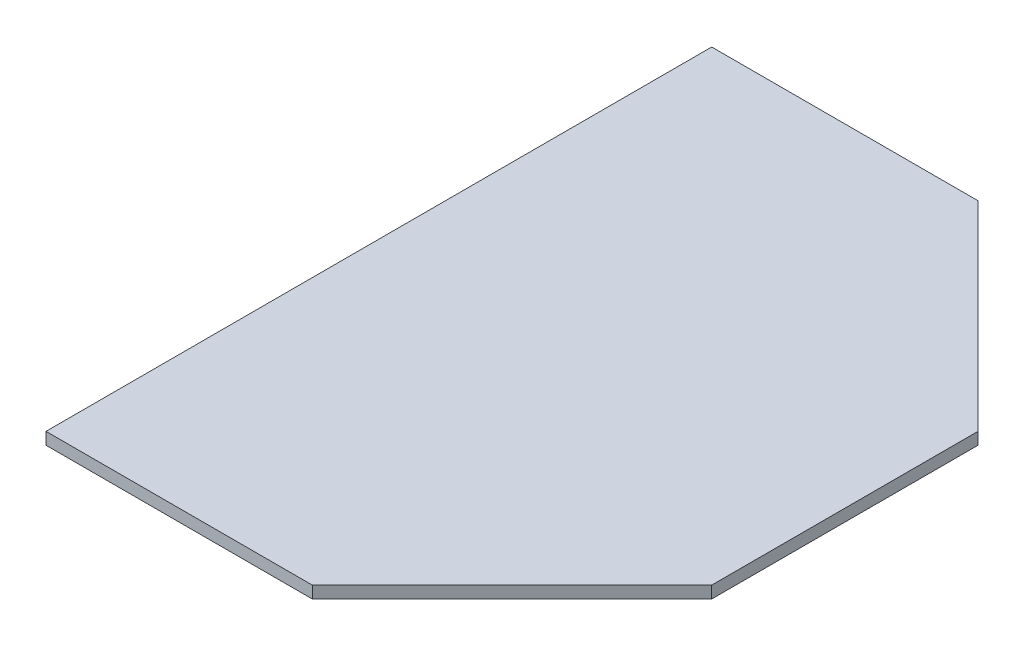
SolidWorks part; units mm, degrees
ref_plane "Front Plane" through (0, 0, 0) normal (0, 0, 1) x (1, 0, 0)
ref_plane "Top Plane" through (0, 0, 0) normal (0, 1, 0) x (1, 0, 0)
ref_plane "Right Plane" through (0, 0, 0) normal (1, 0, 0) x (0, 0, -1)
sketch "Sketch1" plane through (0, 0, 0) normal (0, 1, 0) x (1, 0, 0)
  line L1 (0, 0) -> (254, 0)
  line L2 (0, 0) -> (0, 254)
  line L3 (0, 254) -> (254, 254)
  line L4 (254, 0) -> (254, 254)
  dimension "D1" = 254
  dimension "D2" = 254
extrude "Boss-Extrude1" add sketch "Sketch1" along normal blind 4.6
sketch "Sketch2" plane through (0, 4.6, 0) normal (0, 1, 0) x (1, 0, 0)
  line L0 (0, 254) -> (76.2, 254) construction
  line L1 (254, 254) -> (0, 254) construction
  line L2 (0, 254) -> (0, 177.8) construction
  line L3 (0, 254) -> (0, 0) construction
sketch "Sketch4" plane through (0, 4.6, 0) normal (0, 1, 0) x (1, 0, 0)
  line L0 (76.2, 254) -> (0, 177.8)
  line L1 (0, 177.8) -> (0, 254)
  line L2 (0, 254) -> (76.2, 254)
extrude "Cut-Extrude2" cut sketch "Sketch4" against normal through all
sketch "Sketch5" plane through (0, 4.6, 0) normal (0, 1, 0) x (1, 0, 0)
  line L0 (177.8, 254) -> (254, 254) construction
  line L1 (254, 254) -> (76.2, 254) construction
  line L2 (254, 254) -> (254, 177.8) construction
  line L3 (254, 0) -> (254, 254) construction
  line L4 (177.8, 254) -> (254, 177.8)
  line L5 (254, 177.8) -> (254, 254)
  line L6 (254, 254) -> (177.8, 254)
extrude "Cut-Extrude3" cut sketch "Sketch5" against normal blind 4.826
sketch "Sketch9" plane through (0, 4.6, 0) normal (0, 1, 0) x (1, 0, 0)
  line L0 (0, 76.2) -> (0, 0)
  line L1 (0, 177.8) -> (0, 0) construction
  line L2 (0, 0) -> (76.2, 0)
  line L3 (0, 0) -> (254, 0) construction
  line L4 (76.2, 0) -> (0, 76.2)
  dimension "D1" = 76.2
  dimension "D2" = 76.2
extrude "Cut-Extrude5" cut sketch "Sketch9" against normal blind 4.826
sketch "Sketch11" plane through (0, 4.6, 0) normal (0, 1, 0) x (1, 0, 0)
  line L0 (254, 76.2) -> (254, 0)
  line L1 (254, 0) -> (254, 177.8) construction
  line L2 (254, 0) -> (177.8, 0)
  line L3 (76.2, 0) -> (254, 0) construction
  line L4 (177.8, 0) -> (254, 76.2)
  dimension "D1" = 76.2
  dimension "D2" = 76.2
extrude "Cut-Extrude6" cut sketch "Sketch11" against normal blind 4.826
ref_plane "Plane1" through (0, 0, -127) normal (0, 0, -1) x (-1, 0, 0)
ref_plane "Plane2" through (127, 0, 0) normal (-1, 0, 0) x (0, 0, 1)
sketch "Sketch12" plane through (0, 0, 0) normal (0, -1, 0) x (1, 0, 0)
  line L0 (76.2, 0) -> (76.2, -254)
  line L1 (76.2, -254) -> (0, -177.8)
  line L2 (0, -177.8) -> (0, -76.2)
  line L3 (0, -76.2) -> (76.2, 0)
extrude "Cut-Extrude7" cut sketch "Sketch12" against normal through all
equation "\"MDF\"= 4.8mm"
equation "\"Foamcore\"= 4.6mm"
equation "\"GMaterial\"= \"MDF\""
equation "\"D1@Boss-Extrude1\"=\"Foamcore\""
equation "\"PCB\" = 1.6mm"
equation "\"BaseWidth\" = 10in"
equation "\"SkidLength\" = 1in"
equation "\"SkidClearance\" = 0.4in"
equation "\"MotorMountLength\" = 2in"
equation "\"MotorMountWidth\" = \"GMaterial\""
equation "\"MotorMountHeight\" = 2.25in"
equation "\"UnoStackWidth\" = 77.4mm"
equation "\"UnoStackLength\" = 79.8mm"
equation "\"UnoStackHeight\" = 34.2mm"
equation "\"TallHexRiserHeight\" = 22.2mm"
equation "\"PingPongBallSize\" = 40mm"
equation "\"BarrelLength\" = 9in"
equation "\"BarrelSize\" = \"PingPongBallSize\""
equation "\"PlatformLength\" = 4in"
equation "\"PlatformWidth\" = 6in"
equation "\"WheelDiameter\"=2.99213"
equation "\"ServoMountHeight\"=2.49223"
equation "\"ServoGearHeight\" = 0.95330261in"
equation "\"ServoMountLength\"= 1.53774"
equation "\"PivotHoleRadius\"= 0.616358"
equation "\"PlatformMountHeight\" = 3.19"
equation "\"TensionOffSet\"= .3mm"
equation "\"MotorMountWedge\"=0.333333"
equation "\"LaserCutterOffset\"= .3mm"
equation "\"BumperWidth\"=11"
equation "\"PitcherWheelCompression\" = 2.5mm"
equation "\"PitchingWheelWidth\" = 26.2mm"
equation "\"PitchingWheelDiameter\" = 65.5mm"
equation "\"PitchingWheelMountOffset\" = 8.4mm"
equation "\"PitchingWheelInnerDiameter\" = 45.5mm"
equation "\"PitchingWheelBoltShoulder\" = 4.5mm"
equation "\"BrassCouplingLength\" = 18mm"
equation "\"PitchingMotorHeight\" = 57.0mm"
equation "\"PitchingMotorShaftTopHeight\" = \"PitchingMotorHeight\" - 44.1mm"
equation "\"PitchingMotorBodyHeight\" = 38mm"
equation "\"PitchingMotorTopShoulderHeight\" = 40.6mm - \"PitchingMotorBodyHeight\" "
equation "\"PitchingMotorBottomShoulderHeight\" = 40.2mm - \"PitchingMotorBodyHeight\""
equation "\"PitchingMotorBottomShaftHeight\" = \"PitchingMotorHeight\" - \"PitchingMotorShaftTopHeight\" - \"PitchingMotorTopShoulderHeight\" - \"PitchingMotorBodyHeight\" - \"PitchingMotorBottomShoulderHeight\""
equation "\"PitchingMotorShaftDiameter\" = 2.2mm"
equation "\"PitchingMotorBodyDiameter\" = 27.4mm"
equation "\"PitchingMotorTopShoulderDiameter\" = 9.8mm"
equation "\"PitchingMotorBottomShoulderDiameter\" = 9.8mm"
equation "\"BrassCouplingHexSize\" = 12mm"
equation "\"BrassCouplingBoreSize\" = 3.17mm"
equation "\"PitchingMotorMountingHoleDistance\" = 16mm"
equation "\"Acrylic\" = 4.4mm"
equation "\"PitchingMotorDistance\" = \"PitchingWheelDiameter\" + \"PingPongBallSize\" - \"PitcherWheelCompression\"*2"
equation "\"PitchingMotorPlatformOffset\"=1"
equation "\"ServoPlatformOffset\"=1.64173"
equation "\"BallBearingDiameter\" = 22mm"
equation "\"BallBearingWidth\" = 9mm"
equation "\"BallBearingHexShoulder\" = 9mm - 5.9mm"
equation "\"BallBearingHexSize\" = .36in"
equation "\"PlatformMountFootLength\"=0.857143"
equation "\"WheelWidth\"= 26mm"
equation "\"ServoMountReductionBackHeight\"=2.25"
equation "\"PlatformBottomWidthThird\" =  0.857143in"
equation "\"PlatformMountBackReductionHeight\"= 2.5in"
equation "\"PlatformMountBackReductionWidth\"= 3/7in"
equation "\"PlatformMountFrontReductionWidth\" =  1.46226in"
equation "\"PlatformMountFrontReductionHeight\" = 2.5in"
equation "\"BarrelToHopperDistance\" = 0.5405in"
equation "\"HopperLongWallLength\" = 8.646in"
equation "\"HopperShortWallLength\" = 0.9571in"
equation "\"HopperHeight\" = 3.50in - \"Foamcore\""
equation "\"HoperLongSlantLength\" = 7.064in"
equation "\"HopperBottomTemplateWidth\" = 8.03903165in"
equation "\"HopperBottomTemplateLength\" = 10.367854in"
equation "\"BeaconDiameter\" = 3.45in"
equation "\"HopperTopWidth\" = 11 - \"Foamcore\"*2 - \"BeaconDiameter\""
